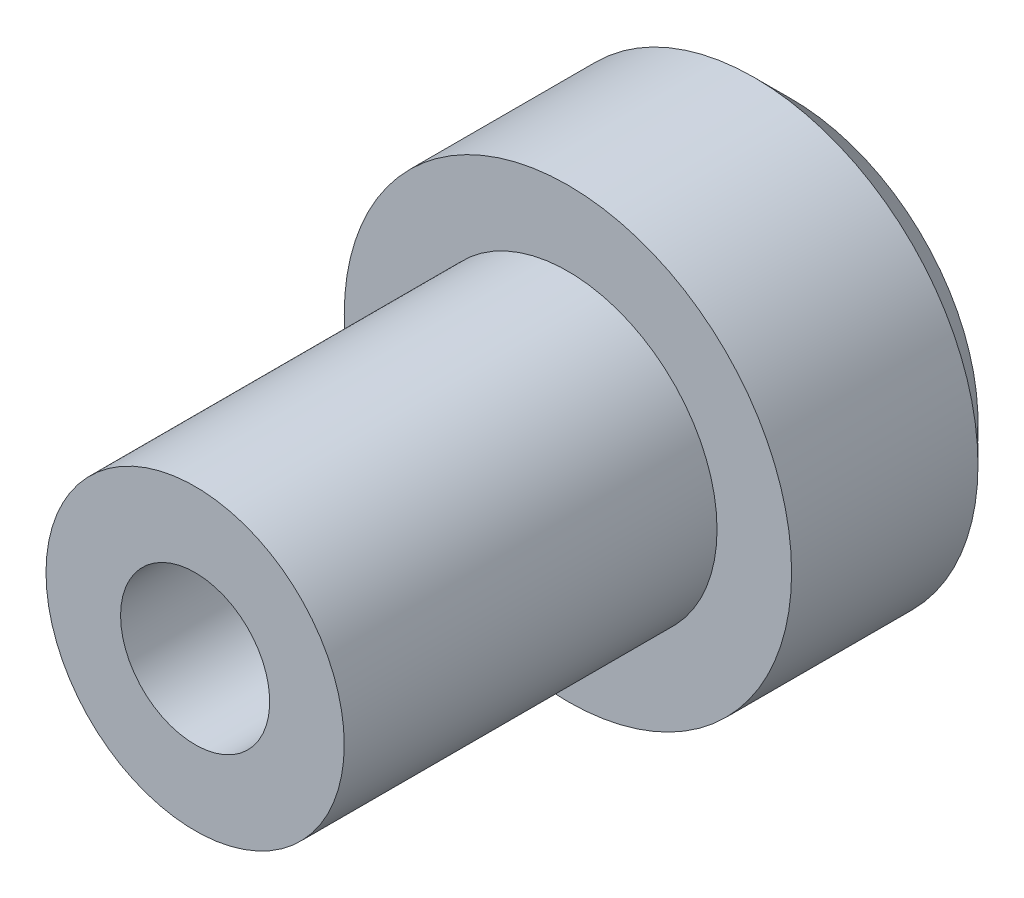
SolidWorks part; units mm, degrees
ref_plane "Front Plane" through (0, 0, 0) normal (0, 0, 1) x (1, 0, 0)
ref_plane "Top Plane" through (0, 0, 0) normal (0, 1, 0) x (1, 0, 0)
ref_plane "Right Plane" through (0, 0, 0) normal (1, 0, 0) x (0, 0, -1)
sketch "Sketch1" plane through (0, 0, 0) normal (0, 0, 1) x (1, 0, 0)
  circle A0 centre (0, 0) radius 2
  dimension "D1" = 4
extrude "Boss-Extrude1" add sketch "Sketch1" along normal blind 5
sketch "Sketch2" plane through (0, 0, 0) normal (0, 0, -1) x (-1, 0, 0)
  circle A0 centre (0, 0) radius 3
extrude "Boss-Extrude2" add sketch "Sketch2" along normal blind 3
chamfer "Chamfer1" distance 0.5 angle 45 1 edges at (-3, 0, -3)
sketch "Sketch5" plane through (0, 0, -3) normal (0, 0, -1) x (-1, 0, 0)
  line L1 (0, -1.1547) -> (1, -0.5774)
  line L2 (1, -0.5774) -> (1, 0.5774)
  line L3 (1, 0.5774) -> (0, 1.1547)
  line L4 (0, 1.1547) -> (-1, 0.5774)
  line L5 (-1, 0.5774) -> (-1, -0.5774)
  line L6 (-1, -0.5774) -> (0, -1.1547)
  circle A0 centre (0, 0) radius 1 construction
  dimension "D1" = 2
extrude "Cut-Extrude3" cut sketch "Sketch5" against normal blind 1.5
sketch "Sketch6" plane through (0, 0, -1.5) normal (0, 0, -1) x (-1, 0, 0)
  circle A0 centre (0, 0) radius 1
  dimension "D1" = 2
extrude "Cut-Extrude4" cut sketch "Sketch6" against normal through all
